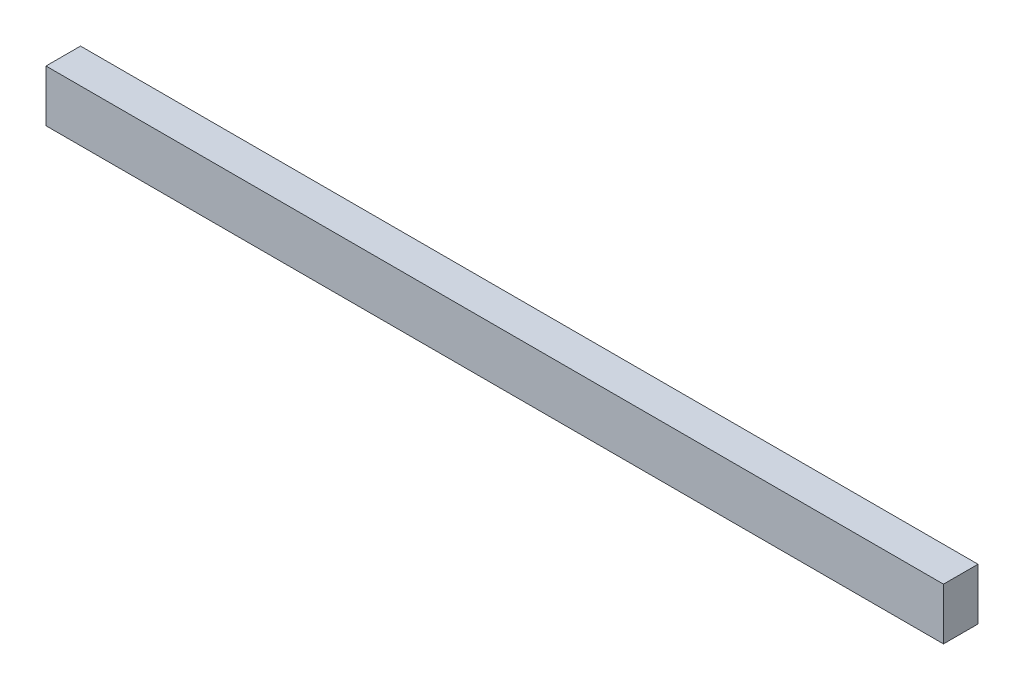
SolidWorks part; units mm, degrees
ref_plane "Front Plane" through (0, 0, 0) normal (0, 0, 1) x (1, 0, 0)
ref_plane "Top Plane" through (0, 0, 0) normal (0, 1, 0) x (1, 0, 0)
ref_plane "Right Plane" through (0, 0, 0) normal (1, 0, 0) x (0, 0, -1)
sketch "Sketch2" plane through (0, 0, 0) normal (0, 0, 1) x (1, 0, 0)
  line L1 (0, 0) -> (26, 0)
  line L2 (0, 0) -> (0, 1.5)
  line L3 (0, 1.5) -> (26, 1.5)
  line L4 (26, 0) -> (26, 1.5)
  dimension "D1" = 1.5
  dimension "D2" = 26
extrude "Boss-Extrude1" add sketch "Sketch2" along normal blind 1 contours L2 L1 L4 L3
